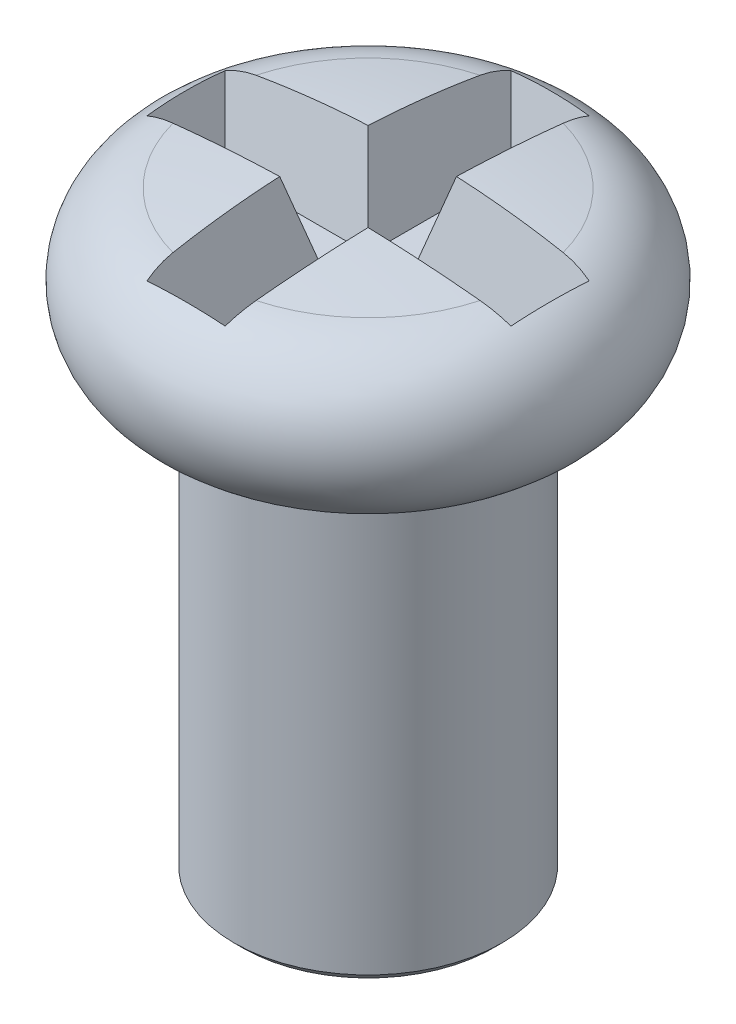
SolidWorks part; units mm, degrees
ref_plane "前视基准面" through (0, 0, 0) normal (0, 0, 1) x (1, 0, 0)
ref_plane "上视基准面" through (0, 0, 0) normal (0, 1, 0) x (1, 0, 0)
ref_plane "右视基准面" through (0, 0, 0) normal (1, 0, 0) x (0, 0, -1)
sketch "草图1" plane through (0, 0, 0) normal (0, 0, 1) x (1, 0, 0)
  line L0 (0, 7.0024) -> (0, -7.0024) construction
  line L1 (0, 0) -> (1.5, 0)
  line L2 (1.5, 0) -> (1.5, 5)
  line L3 (1.5, 5) -> (2.1, 5)
  line L4 (0, 6.8) -> (-0.9395, 6.8) construction
  line L5 (0, 6.8) -> (0, 0)
  arc A0 (1.7808, 6.6699) -> (2.1, 5) centre (1.65, 5.7794) cw
  arc A1 (0, 6.8) -> (1.7808, 6.6699) centre (0, -5.4497) cw
  point P4 (0, 0)
  point P9 (2.3279, 5)
  dimension "D2" = 5.1
  dimension "D4" = 0.9
  dimension "D1" = 3
  dimension "D3" = 1.8
  dimension "D5" = 5
  dimension "D6" = 0.6
revolve "旋转1" add sketch "草图1" angle 360 about L0
ref_plane "基准面1" through (0, 6.8, 0) normal (0, 1, 0) x (1, 0, 0)
sketch "草图2" plane through (0, 6.8, 0) normal (0, 1, 0) x (1, 0, 0)
  line L1 (-2.1, -0.5) -> (2.1, -0.5)
  line L2 (-2.1, -0.5) -> (-2.1, 0.5)
  line L3 (-2.1, 0.5) -> (2.1, 0.5)
  line L4 (2.1, -0.5) -> (2.1, 0.5)
  line L5 (-2.1, -0.5) -> (2.1, 0.5) construction
  line L6 (-2.1, 0.5) -> (2.1, -0.5) construction
  line L7 (-0.5, -2.1) -> (0.5, -2.1)
  line L8 (-0.5, -2.1) -> (-0.5, 2.1)
  line L9 (-0.5, 2.1) -> (0.5, 2.1)
  line L10 (0.5, -2.1) -> (0.5, 2.1)
  line L11 (-0.5, -2.1) -> (0.5, 2.1) construction
  line L12 (-0.5, 2.1) -> (0.5, -2.1) construction
  point P0 (0, 0)
  point P6 (0, 0)
  point P11 (0.5095, 1.9654)
  point P13 (0, 0)
  dimension "D1" = 4.2
  dimension "D2" = 1
extrude "切除-拉伸1" cut sketch "草图2" against normal blind 1 draft 15 contours L8 L9 L10 L7 | L1 L4 L3 L2
chamfer "倒角1" distance 0.1 angle 45 1 edges at (0, 0, 1.5)
